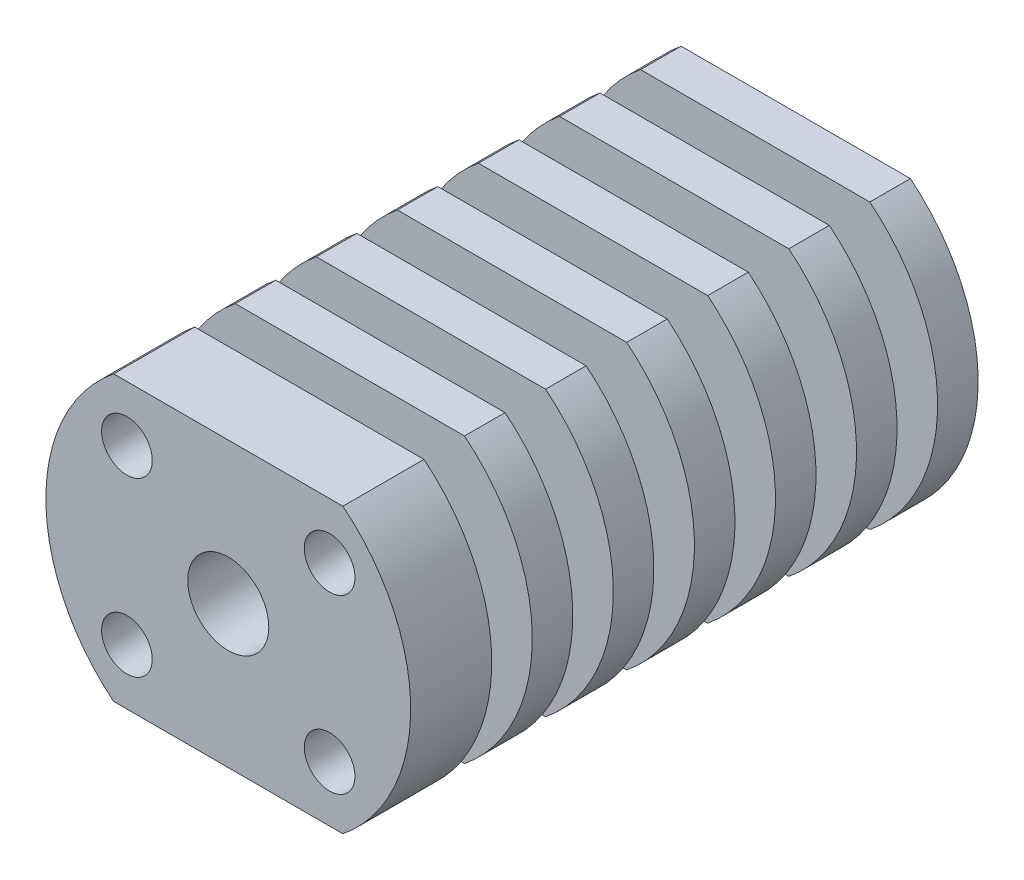
SolidWorks part; units mm, degrees
ref_plane "Piano frontale" through (0, 0, 0) normal (0, 0, 1) x (1, 0, 0)
ref_plane "Piano superiore" through (0, 0, 0) normal (0, 1, 0) x (1, 0, 0)
ref_plane "Piano destro" through (0, 0, 0) normal (1, 0, 0) x (0, 0, -1)
sketch "Schizzo1" plane through (0, 0, 0) normal (0, 0, 1) x (1, 0, 0)
  line L0 (-5.6569, 7) -> (5.6569, 7)
  line L1 (-5.6569, -7) -> (5.6569, -7)
  circle A0 centre (0, 0) radius 9
  dimension "D1" = 18
  dimension "D2" = 14
  dimension "D3" = 7
extrude "Estrusione-Estrusione1" add sketch "Schizzo1" along normal blind 28 contours L0 A0 L1
hole_wizard "Foro filettato M3-1" positions "Schizzo3D1" profile "Schizzo3" tap size "M3" standard "ISO"
sketch3d "Schizzo3D1"
  line L0 (0, 7, 28) -> (0, -7, 28) construction
  line L1 (-5.6569, 7, 28) -> (5.6569, 7, 28) construction
  line L2 (-5.6569, -7, 28) -> (5.6569, -7, 28) construction
  line L5 (0, 0, 28) -> (9, 0, 28) construction
  arc A0 (5.6569, -7, 28) -> (5.6569, 7, 28) centre (0, 0, 28) ccw construction
  point P0 (-5, 4.25, 28)
  point P2 (5, 4.25, 28)
  point P4 (-5, -4.25, 28)
  point P6 (5, -4.25, 28)
  point P28 (0, 0, 37)
  dimension "D1" = 10
  dimension "D2" = 5
  dimension "D3" = 8.5
  dimension "D4" = 4.25
cosmetic thread "Filettatura del foro1" parameters "D1"=2, "D2"=3
cosmetic thread "Filettatura del foro2" parameters "D1"=2, "D2"=3
cosmetic thread "Filettatura del foro3" parameters "D1"=2, "D2"=3
cosmetic thread "Filettatura del foro4" parameters "D1"=2, "D2"=3
sketch "Schizzo3" plane through (-5, 4.25, 28) normal (1, 0, 0) x (0, -1, 0)
  line L0 (0, 0) -> (0, 5.2511)
  line L1 (0, 5.2511) -> (1.25, 4.5)
  line L2 (1.25, 4.5) -> (1.25, 0)
  line L5 (1.25, 0) -> (0, 0)
  line L10 (0, 5.2511) -> (-1.25, 4.5) construction
  line L11 (0, -6.35) -> (0, 107.95) construction
  dimension "Tap Drill Dia." = 2.5
  dimension "Tap Drill Depth" = 4.5
  dimension "Drill Angle" = 118
sketch "Schizzo4" plane through (0, 0, 28) normal (0, 0, 1) x (1, 0, 0)
  circle A0 centre (0, 0) radius 2
extrude "Taglio-Estrusione1" cut sketch "Schizzo4" against normal through all
sketch "Schizzo5" plane through (0, 0, 0) normal (0, 1, 0) x (1, 0, 0)
  line L0 (0, 0) -> (0, -28) construction
  line L1 (3, -24) -> (9, -24)
  line L2 (3, -24) -> (3, -22)
  line L3 (3, -22) -> (9, -22)
  line L4 (9, -24) -> (9, -22)
  line L5 (-2, -28) -> (2, -28) construction
  line L6 (-5.6569, -28) -> (5.6569, -28) construction
  dimension "D1" = 6
  dimension "D2" = 2
  dimension "D3" = 4
  dimension "D4" = 3
revolve "Taglia-Rivoluzione1" cut sketch "Schizzo5" angle 360 about L0
pattern_linear "Ripetizione a L1" count 7 spacing 4 along (0, 0, -1) of "Taglia-Rivoluzione1"
